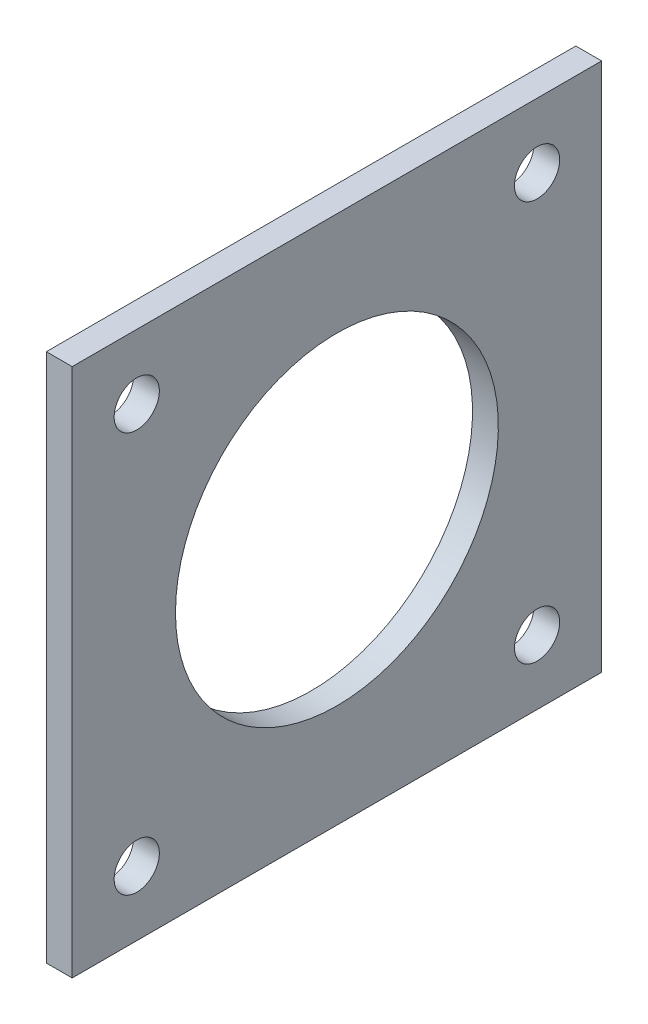
SolidWorks part; units mm, degrees
ref_plane "Front Plane" through (0, 0, 0) normal (0, 0, 1) x (1, 0, 0)
ref_plane "Top Plane" through (0, 0, 0) normal (0, 1, 0) x (1, 0, 0)
ref_plane "Right Plane" through (0, 0, 0) normal (1, 0, 0) x (0, 0, -1)
sketch "Sketch1" plane through (0, 0, 0) normal (0, 1, 0) x (1, 0, 0)
  line L0 (27.5, 55) -> (27.5, 0) construction
  line L1 (5, 0) -> (50, 0)
  line L2 (0, 5) -> (0, 50)
  line L3 (5, 55) -> (50, 55)
  line L4 (55, 5) -> (55, 50)
  line L5 (0, 55) -> (7.5, 55) construction
  line L6 (0, 55) -> (0, 47.5) construction
  line L7 (0, 47.5) -> (7.5, 47.5) construction
  line L8 (7.5, 55) -> (7.5, 47.5) construction
  line L9 (0, 27.5) -> (55, 27.5) construction
  circle A0 centre (7.5, 47.5) radius 2.5
  circle A1 centre (47.5, 47.5) radius 2.5
  circle A2 centre (47.5, 7.5) radius 2.5
  circle A3 centre (7.5, 7.5) radius 2.5
  arc A4 (50, 0) -> (55, 5) centre (50, 5) ccw
  arc A5 (50, 55) -> (55, 50) centre (50, 50) cw
  arc A6 (0, 50) -> (5, 55) centre (5, 50) cw
  arc A7 (5, 0) -> (0, 5) centre (5, 5) cw
  point P23 (55, 55)
  point P29 (0, 0)
  dimension "D3" = 2
  dimension "D5" = 5
  dimension "D1" = 55
  dimension "D2" = 55
  dimension "D4" = 2
extrude "Boss-Extrude2" add sketch "Sketch1" along normal blind 8 and the other way blind 1
sketch "Sketch2" plane through (0, 8, 0) normal (0, 1, 0) x (1, 0, 0)
  line L0 (0, 27.5) -> (55, 27.5)
  line L1 (0, 50) -> (0, 5) construction
  line L2 (55, 5) -> (55, 50) construction
  line L4 (0, 27.5) -> (55, 27.5)
  line L5 (0, 27.5) -> (0, 55)
  line L6 (0, 55) -> (55, 55)
  line L7 (55, 27.5) -> (55, 55)
  circle M3 centre (7.5, 47.5) radius 2.5
  line M5 (55, 5) -> (55, 50)
  arc M6 (55, 50) -> (50, 55) centre (50, 50) ccw
  line M7 (50, 55) -> (5, 55)
  arc M8 (5, 55) -> (0, 50) centre (5, 50) ccw
  line M9 (0, 50) -> (0, 5)
  circle M12 centre (47.5, 47.5) radius 2.5
  dimension "D1" = 27.5
extrude "Cut-Extrude1" cut sketch "Sketch2" against normal through all both and the other way through all contours L0 M9 M5 M6 M7 M8 M12 M3
sketch "Sketch3" plane through (0, 0, -27.5) normal (0, 0, -1) x (-1, 0, 0)
  line L0 (0, -1) -> (0, 8) construction
  line L1 (-55, -1) -> (-37.5, -1) construction
  line L2 (-55, -1) -> (-55, 3.5) construction
  line L3 (-55, 3.5) -> (-37.5, 3.5) construction
  line L4 (-37.5, -1) -> (-37.5, 3.5) construction
  line L5 (0, -1) -> (-55, -1) construction
  circle A0 centre (-37.5, 3.5) radius 3.25
  circle A1 centre (-17.5, 3.5) radius 3.25
  point P10 (0, 3.5)
  dimension "D3" = 6.5
  dimension "D4" = 2
  dimension "D5" = 17.5
  dimension "D1" = 4.5
  dimension "D2" = 17.5
  dimension "D6" = 4.5
sketch3d "3DSketch1"
  point P0 (9.6264, 4.1069, -27.5)
sketch "Sketch5" plane through (0, 8, 0) normal (0, 1, 0) x (1, 0, 0)
  line L0 (27.5, 27.5) -> (27.5, 0)
  line L1 (0, 27.5) -> (55, 27.5) construction
  line L2 (5, 0) -> (50, 0) construction
  line L3 (27.5, 27.5) -> (27.5, 24)
  line L5 (27.5, 24) -> (23, 24)
  line L6 (27.5, 24) -> (27.5, 17.5)
  line L7 (27.5, 17.5) -> (23, 17.5)
  line L8 (23, 24) -> (23, 17.5)
  line L9 (27.5, 24) -> (32, 24)
  line L10 (27.5, 24) -> (27.5, 17.5)
  line L11 (27.5, 17.5) -> (32, 17.5)
  line L12 (32, 24) -> (32, 17.5)
  dimension "D1" = 3.5
  dimension "D2" = 6.5
  dimension "D3" = 4.5
  dimension "D4" = 4.5
  dimension "D5" = 6.5
extrude "Cut-Extrude5" cut sketch "Sketch3" against normal blind 15 draft 0.057 contours A0 | A1
extrude "Boss-Extrude3" add sketch "Sketch5" along normal blind 14.5 contours L5 L8 L7 L0 | L12 L9 L0 L11
sketch "Sketch6" plane through (0, 0, -24) normal (0, 0, -1) x (-1, 0, 0)
  line L0 (-27.5, 8) -> (-27.5, 17)
  line L1 (-32, 8) -> (-23, 8) construction
  circle A0 centre (-27.5, 17) radius 4
  dimension "D2" = 8
  dimension "D1" = 9
extrude "Cut-Extrude4" cut sketch "Sketch6" against normal blind 1.5
sketch "Sketch11" plane through (0, 0, -24) normal (0, 0, -1) x (-1, 0, 0)
  line L0 (-27.5, 22.5) -> (-25.5, 22.5)
  line L1 (-32.4368, 26) -> (-22.5632, 26)
  line L2 (-32, 22.5) -> (-23, 22.5) construction
  line L3 (-25.5, 22.5) -> (-27.5, 22.5)
  line L4 (-25.5, 22.5) -> (-29.5, 22.5)
  line L5 (-25.5, 22.5) -> (-25.5, 26)
  line L6 (-25.5, 26) -> (-29.5, 26)
  line L7 (-29.5, 22.5) -> (-29.5, 26)
  line L8 (-22.5632, 26) -> (-25.5, 22.5)
  line L9 (-29.5, 22.5) -> (-32.4368, 26)
  point P10 (-27.5, 26)
  line M9 (-23, 22.5) -> (-32, 22.5)
  dimension "D1" = 2
  dimension "D2" = 4
  dimension "D3" = 3.5
  dimension "D4" = 40
sketch "Sketch12" plane through (0, 8, 0) normal (0, 1, 0) x (1, 0, 0)
  line L0 (27.5, 17.5) -> (27.5, 0)
  line L1 (32, 17.5) -> (23, 17.5) construction
  line L2 (5, 0) -> (50, 0) construction
  line L3 (17, 0) -> (17, -30)
  line L4 (17, 0) -> (38, 0)
  line L5 (27.5, 0) -> (27.5, -30)
  line L6 (17, -30) -> (38, -30)
  line L7 (38, 0) -> (38, -30)
  point P9 (23.9675, 0)
  line M9 (5, 0) -> (50, 0)
  dimension "D1" = 30
  dimension "D2" = 10.5
extrude "Boss-Extrude7" add sketch "Sketch12" against normal blind 9 contours L7 L5 L6 M9 | L3 L6 L5 M9
sketch "Sketch15" plane through (0, 22.5, 0) normal (0, 1, 0) x (1, 0, 0)
  line L0 (32, 24) -> (32, 17.5) construction
  line L1 (32, 17.5) -> (23, 17.5)
  line L2 (32, 17.5) -> (32, 24)
  line L3 (32, 24) -> (23, 24)
  line L4 (23, 17.5) -> (23, 24)
  line L5 (32, 17.5) -> (23, 17.5) construction
extrude "Boss-Extrude8" add sketch "Sketch15" along normal blind 3.5
extrude "Boss-Extrude9" add sketch "Sketch11" against normal blind 54 contours L9 L7 L1 | L7 L5 L1 M9 | L8 L1 L5
fillet "Fillet4" radius 5 1 edges at (27.5, -1, 30)
sketch "Sketch18" plane through (0, 26, 0) normal (0, 1, 0) x (1, 0, 0)
  line L0 (32.4368, -30) -> (32.4368, 24) construction
  line L1 (22.5632, 24) -> (32.4368, 24)
  line L2 (22.5632, 24) -> (22.5632, 17.5)
  line L3 (22.5632, 17.5) -> (32.4368, 17.5)
  line L4 (32.4368, 24) -> (32.4368, 17.5)
  dimension "D1" = 6.5
extrude "Boss-Extrude11" add sketch "Sketch18" along normal blind 0.5
sketch "Sketch20" plane through (0, 8, 0) normal (0, 1, 0) x (1, 0, 0)
  line L0 (27.5, -1030) -> (27.5, 48970) construction
  line L1 (17, -30) -> (38, -30) construction
  line L2 (32, 17.5) -> (23, 17.5) construction
  line L3 (27.5, 17.5) -> (16.5, 17.5)
  line L4 (27.5, 17.5) -> (27.5, 0)
  line L5 (27.5, 0) -> (16.5, 0)
  line L6 (16.5, 17.5) -> (16.5, 0)
  line L7 (27.5, 17.5) -> (16.5, 0) construction
  line L8 (27.5, 0) -> (16.5, 17.5) construction
  line L10 (27.5, 17.5) -> (38.5, 17.5)
  line L11 (27.5, 17.5) -> (27.5, 0)
  line L12 (27.5, 0) -> (38.5, 0)
  line L13 (38.5, 17.5) -> (38.5, 0)
  line L14 (27.5, 17.5) -> (38.5, 0) construction
  line L15 (27.5, 0) -> (38.5, 17.5) construction
  line L16 (38.5, 17.5) -> (42.5, 17.5)
  line L17 (38.5, 17.5) -> (38.5, 0)
  line L18 (38.5, 0) -> (42.5, 0)
  line L19 (42.5, 17.5) -> (42.5, 0)
  line L21 (16.5, 17.5) -> (12.5, 17.5)
  line L22 (16.5, 17.5) -> (16.5, 0)
  line L23 (16.5, 0) -> (12.5, 0)
  line L24 (12.5, 17.5) -> (12.5, 0)
  line L26 (42.5, 0) -> (38.5, 0)
  line L27 (42.5, 0) -> (42.5, 17.5)
  line L28 (42.5, 17.5) -> (38.5, 17.5)
  line L29 (38.5, 0) -> (38.5, 17.5)
  line L30 (16.5, 0) -> (12.5, 0)
  line L31 (16.5, 0) -> (16.5, 17.5)
  line L32 (16.5, 17.5) -> (12.5, 17.5)
  line L33 (12.5, 0) -> (12.5, 17.5)
  point P5 (27.5, -30)
  point P9 (22, 8.75)
  point P14 (33, 8.75)
  line M12 (5, 0) -> (17, 0)
  line M16 (38, 0) -> (50, 0)
  dimension "D2" = 11
  dimension "D3" = 17.5
  dimension "D4" = 4
extrude "Boss-Extrude12" add sketch "Sketch20" along normal blind 18 contours L21 L24 L6 M12 | L19 L16 L13 M16
sketch "Sketch21" plane through (12.5, 0, 0) normal (-1, 0, 0) x (0, 0, 1)
  line L0 (-17.5, 26) -> (-17.5, 8) construction
  line L1 (0, 26) -> (-17.5, 26)
  line L2 (0, 26) -> (0, 24)
  line L3 (0, 24) -> (-17.5, 24)
  line L4 (-17.5, 26) -> (-17.5, 24)
  dimension "D1" = 2
sketch "Sketch22" plane through (12.5, 0, 0) normal (-1, 0, 0) x (0, 0, 1)
  line L1 (-17.5, 24) -> (0, 24)
  line L2 (-17.5, 24) -> (-17.5, 28)
  line L3 (-17.5, 28) -> (0, 28)
  line L4 (0, 24) -> (0, 28)
  dimension "D1" = 4
extrude "Boss-Extrude13" add sketch "Sketch22" along normal blind 11 and the other way blind 4 contours L3 L4 L1 L2
sketch "Sketch25" plane through (0, 28, 0) normal (0, 1, 0) x (1, 0, 0)
  line L2 (1.5, 17.5) -> (16.5, 17.5) construction
  line L3 (1.5, 0) -> (3.5, 0)
  line L4 (1.5, 0) -> (1.5, 17.5)
  line L5 (1.5, 17.5) -> (3.5, 17.5)
  line L6 (3.5, 0) -> (3.5, 17.5)
  dimension "D1" = 2
extrude "Boss-Extrude14" add sketch "Sketch25" along normal blind 41
sketch "Sketch28" plane through (1.5, 0, 0) normal (-1, 0, 0) x (0, 0, 1)
  line L2 (0, 69) -> (-41, 69)
  line L3 (0, 69) -> (0, 24)
  line L4 (0, 24) -> (-41, 24)
  line L5 (-41, 69) -> (-41, 24)
  dimension "D1" = 45
  dimension "D2" = 41
extrude "Boss-Extrude15" add sketch "Sketch28" against normal blind 2
sketch "Sketch29" plane through (1.5, 0, 0) normal (-1, 0, 0) x (0, 0, 1)
  line L1 (0, 24) -> (-5, 24)
  line L2 (0, 24) -> (0, 33)
  line L3 (0, 33) -> (-5, 33)
  line L4 (-5, 24) -> (-5, 33)
  circle A0 centre (-5, 33) radius 1.75
  circle A1 centre (-36, 33) radius 1.75
  circle A2 centre (-36, 64) radius 1.75
  circle A3 centre (-5, 64) radius 1.75
  dimension "D3" = 3.5
  dimension "D6" = 31
  dimension "D1" = 9
  dimension "D2" = 5
  dimension "D7" = 31
  dimension "D4" = 2
  dimension "D5" = 2
extrude "Cut-Extrude8" cut sketch "Sketch29" against normal blind 9 contours A1 | A3 | A0 | A2
sketch "Sketch30" plane through (42.5, 0, 0) normal (1, 0, 0) x (0, 0, -1)
  line L0 (17.5, 26) -> (17.5, 8) construction
  line L1 (0, 26) -> (17.5, 26)
  line L2 (0, 26) -> (0, 24)
  line L3 (0, 24) -> (17.5, 24)
  line L4 (17.5, 26) -> (17.5, 24)
  line L6 (0, 24) -> (17.5, 24)
  line L7 (0, 24) -> (0, 28)
  line L8 (0, 28) -> (17.5, 28)
  line L9 (17.5, 24) -> (17.5, 28)
  line M4 (17.5, 8) -> (17.5, 26)
  line M5 (17.5, 26) -> (0, 26)
  line M6 (0, 26) -> (0, 8)
  dimension "D1" = 2
  dimension "D2" = 4
extrude "Boss-Extrude16" add sketch "Sketch30" along normal blind 9 and the other way blind 4 contours L3 M6 M4 M5 | L9 L8 L7 M5
sketch "Sketch31" plane through (3.5, 0, 0) normal (1, 0, 0) x (0, 0, -1)
  line L1 (41, 69) -> (20.5, 69)
  line L2 (41, 69) -> (41, 47)
  line L3 (41, 47) -> (20.5, 47)
  line L4 (20.5, 69) -> (20.5, 47)
  circle A0 centre (20.5, 47) radius 10
  dimension "D3" = 20
  dimension "D1" = 22
  dimension "D2" = 20.5
extrude "Cut-Extrude9" cut sketch "Sketch31" against normal blind 9 contours L4 A0 L3 | L3 A0 L4
sketch "Sketch32" plane through (0, 0, -17.5) normal (0, 0, -1) x (-1, 0, 0)
  line L1 (-16.5, 28) -> (-3.5, 28)
  line L2 (-16.5, 28) -> (-16.5, 24)
  line L3 (-16.5, 24) -> (-3.5, 24)
  line L4 (-3.5, 28) -> (-3.5, 24)
extrude "Boss-Extrude17" add sketch "Sketch32" along normal blind 23.5
sketch "Sketch33" plane through (0, 8, 0) normal (0, 1, 0) x (1, 0, 0)
  line L0 (38.5, 17.5) -> (38.5, 0)
  line L1 (38.5, 17.5) -> (38, 17.5)
  line L2 (38.5, 0) -> (38, 0)
  line L3 (38, 17.5) -> (38, 0)
  line L4 (16.5, 17.5) -> (16.5, 0)
  line L5 (16.5, 17.5) -> (17, 17.5)
  line L6 (16.5, 0) -> (17, 0)
  line L7 (17, 17.5) -> (17, 0)
  dimension "D1" = 0.5
  dimension "D2" = 0.5
extrude "Boss-Extrude18" add sketch "Sketch33" along normal blind 20
sketch "Sketch34" plane through (0, 0, 0) normal (0, 0, 1) x (1, 0, 0)
  line L0 (42.5, 24) -> (42.5, 8) construction
  line L1 (51.5, 28) -> (42.5, 28)
  line L2 (51.5, 28) -> (51.5, 24)
  line L3 (51.5, 24) -> (42.5, 24)
  line L4 (42.5, 28) -> (42.5, 24)
  line L5 (42.5, 24) -> (51.5, 24) construction
  line L7 (42.5, 28) -> (38, 28)
  line L8 (42.5, 28) -> (42.5, -1)
  line L9 (42.5, -1) -> (38, -1)
  line L10 (38, 28) -> (38, -1)
  line L11 (17, 28) -> (1.5, 28)
  line L12 (17, 28) -> (17, 24)
  line L13 (17, 24) -> (1.5, 24)
  line L14 (1.5, 28) -> (1.5, 24)
  line L15 (12.5, 24) -> (17, 24)
  line L16 (12.5, 24) -> (12.5, -1)
  line L17 (12.5, -1) -> (17, -1)
  line L18 (17, 24) -> (17, -1)
  line M1 (42.5, 8) -> (42.5, 24)
  line M2 (42.5, 24) -> (51.5, 24)
  line M3 (51.5, 24) -> (51.5, 28)
  line M4 (51.5, 28) -> (38, 28)
  line M5 (38, 28) -> (38, 8)
  line M6 (38, 8) -> (38, -1)
  line M7 (38, -1) -> (50, -1)
extrude "Boss-Extrude19" add sketch "Sketch34" along normal blind 26 contours L18 L13 L16 L17 | L11 L14 L13 L12 | L8 L4 M1 M4 M5 M6 M7 | L4 M4 M2 M3
sketch "Sketch35" plane through (0, 0, -17.5) normal (0, 0, 1) x (1, 0, 0)
  line L1 (32.4368, 26.5) -> (22.5632, 26.5)
  line L2 (32.4368, 26.5) -> (32.4368, 26)
  line L3 (32.4368, 26) -> (22.5632, 26)
  line L4 (22.5632, 26.5) -> (22.5632, 26)
extrude "Boss-Extrude20" add sketch "Sketch35" along normal blind 47.5
sketch "Sketch37" plane through (0, 0, -17.5) normal (0, 0, 1) x (1, 0, 0)
  line L0 (27.5, 8) -> (29.5, 8)
  line L2 (32, 8) -> (23, 8) construction
  line L3 (29.5, 12) -> (33.1362, 7.6666)
  line L4 (29.5, 8) -> (25.5, 8)
  line L5 (29.5, 8) -> (29.5, 12)
  line L6 (29.5, 12) -> (25.5, 12)
  line L7 (25.5, 8) -> (25.5, 12)
  line L8 (25.5, 12) -> (21.8638, 7.6666)
  line L9 (21.8638, 7.6666) -> (33.1362, 7.6666)
  line M8 (32, 8) -> (32, 25.4794)
  line M12 (23, 25.4794) -> (23, 8)
  line M13 (23, 8) -> (32, 8)
  dimension "D1" = 2
  dimension "D2" = 4
  dimension "D3" = 4
  dimension "D4" = 40
  dimension "D5" = 40
extrude "Boss-Extrude21" add sketch "Sketch37" along normal blind 47.5 contours L7 L8 M12 M13 | L7 L5 L6 M13 | L5 L3 M13 M8 | L8 L9 L3 M8 M13 M12
sketch "Sketch38" plane through (0, 0, 30) normal (0, 0, 1) x (1, 0, 0)
  line L1 (22.5632, 26.5) -> (22.1436, 26.5)
  line L2 (22.5632, 26.5) -> (22.5632, 8)
  line L3 (22.5632, 8) -> (22.1436, 8)
  line L4 (22.1436, 26.5) -> (22.1436, 8)
  line L5 (32.4368, 26.5) -> (32.8564, 26.5)
  line L6 (32.4368, 26.5) -> (32.4368, 8)
  line L7 (32.4368, 8) -> (32.8564, 8)
  line L8 (32.8564, 26.5) -> (32.8564, 8)
extrude "Cut-Extrude10" cut sketch "Sketch38" against normal blind 90.5
sketch "Sketch39" plane through (0, 0, 30) normal (0, 0, 1) x (1, 0, 0)
  line L0 (27.784, 26.1035) -> (27.5, 26.5)
  line L1 (32.4368, 26.5) -> (38, 26.5)
  line L2 (32.4368, 26.5) -> (32.4368, 8)
  line L3 (32.4368, 8) -> (38, 8)
  line L4 (38, 26.5) -> (38, 8)
  line L5 (32.4368, 26.5) -> (22.5632, 26.5) construction
  line L6 (27.5, 26.5) -> (27.5, 8)
  line L7 (38, 17.25) -> (38, 19.25)
  line L8 (34, 19.25) -> (38, 22.6064)
  line L9 (38, 19.25) -> (34, 19.25)
  line L10 (38, 19.25) -> (38, 15.25)
  line L11 (38, 15.25) -> (34, 15.25)
  line L12 (34, 19.25) -> (34, 15.25)
  line L13 (34, 15.25) -> (38, 11.8936)
  line L14 (22.5632, 8.5) -> (21.9673, 8)
  line L15 (17, 8) -> (22.5632, 8) construction
  line L16 (17, 22.6064) -> (17.7151, 22.6064)
  line L17 (38, 22.6064) -> (37.2849, 22.6064)
  line L18 (38, 22.6064) -> (38, 22.0064)
  line L19 (38, 22.0064) -> (37.2849, 22.0064)
  line L20 (37.2849, 22.6064) -> (37.2849, 22.0064)
  line L21 (38, 11.8936) -> (37.2849, 11.8936)
  line L22 (38, 11.8936) -> (38, 12.4936)
  line L23 (38, 12.4936) -> (37.2849, 12.4936)
  line L24 (37.2849, 11.8936) -> (37.2849, 12.4936)
  line L25 (17.7151, 22.6064) -> (17.7151, 22.0064)
  line L26 (17, 22.0064) -> (17.7151, 22.0064)
  line L27 (21, 19.25) -> (17, 22.6064)
  line L28 (21, 19.25) -> (21, 15.25)
  line L29 (17, 19.25) -> (21, 19.25)
  line L30 (17.7151, 11.8936) -> (17.7151, 12.4936)
  line L31 (17, 11.8936) -> (17.7151, 11.8936)
  line L32 (17, 12.4936) -> (17.7151, 12.4936)
  line L33 (17, 26.5) -> (17, 8)
  line L34 (17, 15.25) -> (21, 15.25)
  line L35 (21, 15.25) -> (17, 11.8936)
  line L36 (17, 19.25) -> (17, 22.0064)
  line L37 (17, 22.0064) -> (17.7151, 22.0064)
  line L38 (17.7151, 22.0064) -> (21, 19.25)
  line L39 (17, 19.25) -> (21, 19.25)
  dimension "D1" = 2
  dimension "D2" = 4
  dimension "D3" = 4
  dimension "D4" = 40
  dimension "D5" = 40
  dimension "D6" = 0.6
  dimension "D7" = 0.6
extrude "Boss-Extrude23" add sketch "Sketch39" against normal blind 47.5 contours L26 L33 L29 L27 | L33 L34 L28 L29 | L35 L34 L33 L32 | L23 L4 L11 L13 | L9 L12 L11 L4 | L4 L19 L8 L9
ref_plane "Plane1" through (5, 8, 0) normal (0, 1, 0) x (1, 0, 0)
sketch "Sketch45" plane through (0, 8, 0) normal (0, 1, 0) x (1, 0, 0)
  line L0 (0, 15.4413) -> (0, -89.262) construction
  line L1 (-11, 15.4413) -> (-11, -89.262)
  dimension "D1" = 11
sketch "Sketch46" plane through (0, 0, 0) normal (-1, 0, 0) x (0, 0, 1)
  line L1 (-27.5, -1) -> (-5, -1)
  line L2 (-27.5, -1) -> (-27.5, 8)
  line L3 (-27.5, 8) -> (-5, 8)
  line L4 (-5, -1) -> (-5, 8)
  line L5 (-27.5, 8) -> (0, 8)
  line L6 (-27.5, 8) -> (-27.5, -1)
  line L7 (-27.5, -1) -> (0, -1)
  line L8 (0, 8) -> (0, -1)
  line M2 (-27.5, 8) -> (-27.5, -1)
  line M3 (-27.5, -1) -> (-5, -1)
  line M4 (-5, -1) -> (-5, 8)
  line M5 (-5, 8) -> (-27.5, 8)
  dimension "D1" = 27.5
extrude "Boss-Extrude26" add sketch "Sketch46" against normal blind 11.5 contours M5 M2 M3 M4 | L8 L5 L7 M4
sketch "Sketch47" plane through (0, 0, 0) normal (-1, 0, 0) x (0, 0, 1)
  line L1 (-27.5, 8) -> (0, 8)
  line L2 (-27.5, 8) -> (-27.5, -1)
  line L3 (-27.5, -1) -> (0, -1)
  line L4 (0, 8) -> (0, -1)
extrude "Boss-Extrude27" add sketch "Sketch47" along normal blind 11
sketch "Sketch48" plane through (0, 8, 0) normal (0, 1, 0) x (1, 0, 0)
  line L0 (12.5, 17.5) -> (12.5, 24)
  line L1 (23, 24) -> (12.5, 24)
  line L2 (23, 24) -> (23, 17.5)
  line L3 (23, 17.5) -> (12.5, 17.5)
  line L4 (12.5, 24) -> (12.5, 17.5)
  line L5 (12.5, 17.5) -> (7.5, 17.5)
  line L6 (12.5, 24) -> (7.5, 24)
  line L7 (7.5, 17.5) -> (7.5, 24)
  line L8 (42.5, 24) -> (42.5, 17.5)
  line L9 (32, 24) -> (42.5, 24)
  line L10 (32, 24) -> (32, 17.5)
  line L11 (32, 17.5) -> (42.5, 17.5)
  line L12 (42.5, 24) -> (42.5, 17.5)
  line L13 (42.5, 24) -> (47.5, 24)
  line L14 (42.5, 17.5) -> (47.5, 17.5)
  line L15 (47.5, 24) -> (47.5, 17.5)
  line M3 (12.5, 17.5) -> (17, 17.5)
  line M8 (22.5632, 17.5) -> (23, 17.5)
  line M9 (23, 17.5) -> (23, 24)
  line M11 (32, 24) -> (32, 17.5)
  line M12 (32, 17.5) -> (32.4368, 17.5)
  line M17 (38, 17.5) -> (42.5, 17.5)
  dimension "D1" = 5
  dimension "D2" = 5
sketch "Sketch49" plane through (0, 0, -24) normal (0, 0, -1) x (-1, 0, 0)
  line L0 (-17.5, 3.5) -> (-27.5, 17)
  line L1 (-27.5, 17) -> (-17.5, 17)
  line L2 (-17.5, 17) -> (-17.5, 3.5)
  line L3 (-27.5, 17) -> (-37.5, 3.5)
  line L4 (-37.5, 3.5) -> (-37.5, 17)
  line L5 (-37.5, 17) -> (-27.5, 17)
  circle A0 centre (-37.5, 17) radius 4
  circle A1 centre (-17.5, 17) radius 4
  dimension "D1" = 8
  dimension "D2" = 8
extrude "Boss-Extrude31" add sketch "Sketch48" along normal blind 18.5 contours L11 L8 L9 M12 M17 M11 | L15 L13 L8 L14 | L3 L1 L0 M8 M9 M3 | L7 L5 L0 L6
sketch "Sketch50" plane through (0, 0, -24) normal (0, 0, -1) x (-1, 0, 0)
  circle A0 centre (-17.5, 17) radius 4
  circle A1 centre (-37.5, 17) radius 4
  dimension "D1" = 8
  dimension "D2" = 8
extrude "Cut-Extrude11" cut sketch "Sketch50" against normal blind 1.5
sketch "Sketch51" plane through (0, 0, -24) normal (0, 0, -1) x (-1, 0, 0)
  line L1 (-32.4593, 12.5515) -> (-22.8331, 12.5515)
  line L2 (-32.4593, 12.5515) -> (-32.4593, 21.6767)
  line L3 (-32.4593, 21.6767) -> (-22.8331, 21.6767)
  line L4 (-22.8331, 12.5515) -> (-22.8331, 21.6767)
extrude "Boss-Extrude32" add sketch "Sketch51" against normal blind 1.5
sketch "Sketch53" plane through (0, 0, -24) normal (0, 0, -1) x (-1, 0, 0)
  line L0 (-27.5, 17) -> (-27.5, 8)
  line L1 (-47.5, 8) -> (-7.5, 8) construction
  line L2 (-27.5, 8) -> (-27.5, 26.5)
  line L3 (-47.5, 26.5) -> (-16.5, 26.5) construction
  line L4 (-27.5, 17.25) -> (-23.5, 17.25)
  line L5 (-23.5, 17.25) -> (-31.5, 17.25)
  line L7 (-31.5, 13.25) -> (-23.5, 13.25)
  line L8 (-31.5, 13.25) -> (-31.5, 21.25)
  line L9 (-31.5, 21.25) -> (-23.5, 21.25)
  line L10 (-23.5, 13.25) -> (-23.5, 21.25)
  line L11 (-31.5, 13.25) -> (-23.5, 21.25) construction
  line L12 (-31.5, 21.25) -> (-23.5, 13.25) construction
  dimension "D1" = 4
  dimension "D2" = 4
  dimension "D3" = 8
  dimension "D4" = 8
sketch "Sketch54" plane through (0, 0, -17.5) normal (0, 0, 1) x (1, 0, 0)
  line L0 (27.5, 22.5) -> (27.5, 14.5)
  line L1 (29.5, 22.5) -> (25.5, 22.5) construction
  line L3 (23.5, 22.5) -> (31.5, 22.5)
  line L4 (23.5, 22.5) -> (23.5, 14.5)
  line L5 (23.5, 14.5) -> (31.5, 14.5)
  line L6 (31.5, 22.5) -> (31.5, 14.5)
  line L7 (23.5, 22.5) -> (31.5, 14.5) construction
  line L8 (23.5, 14.5) -> (31.5, 22.5) construction
  point P4 (27.5, 18.5)
  line M17 (29.5, 22.5) -> (25.5, 22.5)
  dimension "D1" = 8
  dimension "D2" = 8
  dimension "D3" = 8
extrude "Boss-Extrude35" add sketch "Sketch54" along normal blind 47.5 contours L6 L3 L0 L5 M17 | L4 L5 L0 L3 M17
sketch "Sketch55" plane through (0, 0, 30) normal (0, 0, 1) x (1, 0, 0)
  line L1 (32.4368, 26.5) -> (22.5632, 26.5)
  line L2 (32.4368, 26.5) -> (32.4368, 26)
  line L3 (32.4368, 26) -> (22.5632, 26)
  line L4 (22.5632, 26.5) -> (22.5632, 26)
extrude "Cut-Extrude12" cut sketch "Sketch55" against normal blind 47.5
sketch "Sketch56" plane through (0, 0, 26) normal (0, 0, 1) x (1, 0, 0)
  line L1 (38, 28) -> (37.5, 28)
  line L2 (38, 28) -> (38, 8)
  line L3 (38, 8) -> (37.5, 8)
  line L4 (37.5, 28) -> (37.5, 8)
  line L5 (17, 28) -> (17.5, 28)
  line L6 (17, 28) -> (17, 8)
  line L7 (17, 8) -> (17.5, 8)
  line L8 (17.5, 28) -> (17.5, 8)
  dimension "D1" = 0.5
  dimension "D2" = 0.5
extrude "Boss-Extrude36" add sketch "Sketch56" against normal blind 43.5
sketch "Sketch57" plane through (0, 0, 30) normal (0, 0, 1) x (1, 0, 0)
  line L0 (31.5, 20.5) -> (31.5, 16.5)
  line L1 (35, 18.4644) -> (35, 13.5632)
  line L2 (25.5, 22.5) -> (29.5, 22.5)
  line L3 (29.5, 22.5) -> (32.4368, 26)
  line L4 (29.5, 22.5) -> (29.5, 26)
  line L5 (22.5632, 26) -> (32.4368, 26) construction
  line L6 (31.5, 22.5) -> (31.5, 14.5) construction
  line L7 (35, 13.5632) -> (31.5, 16.5)
  line L8 (31.5, 16.5) -> (35, 16.5)
  line L9 (31.5, 16.5) -> (31.5, 20.4288)
  line L10 (31.5, 20.4288) -> (35, 20.4288)
  line L11 (35, 16.5) -> (35, 20.4288)
  line L12 (35, 18.5356) -> (35, 23.4368)
  line L13 (35, 16.5) -> (31.5, 16.5)
  line L14 (35, 16.5) -> (35, 18.5)
  line L15 (35, 18.5) -> (31.5, 18.5)
  line L16 (31.5, 16.5) -> (31.5, 18.5)
  line L17 (35, 23.4368) -> (31.5, 20.5)
  line L18 (27.5, 22.5) -> (27.5, 14.5) construction
  line L19 (23.5, 14.5) -> (31.5, 14.5) construction
  line L20 (20, 13.5632) -> (23.5, 16.5)
  line L21 (23.5, 16.5) -> (20, 16.5)
  line L22 (20, 18.4644) -> (20, 13.5632)
  line L23 (20, 18.5356) -> (20, 23.4368)
  line L24 (20, 23.4368) -> (23.5, 20.5)
  line L25 (23.5, 20.5) -> (23.5, 16.5)
  line L26 (27.5, 18.5) -> (31.5, 18.5) construction
  line L27 (31.5, 18.5) -> (23.5, 18.5) construction
  line L28 (23.5, 20.5) -> (23.5, 16.5)
  line L29 (32.4368, 26) -> (22.5632, 26)
  line L30 (22.5632, 26) -> (25.5, 22.5)
  line L31 (25.5, 14.5) -> (29.5, 14.5)
  line L32 (22.5632, 11) -> (25.5, 14.5)
  line L33 (32.4368, 11) -> (22.5632, 11)
  line L34 (29.5, 14.5) -> (32.4368, 11)
  line L35 (23.5, 16.5) -> (20, 13.5632)
  line L36 (20, 13.5632) -> (20, 23.4368)
  line L37 (20, 23.4368) -> (23.5, 20.5)
  line L38 (23.5, 18.5) -> (23.5, 20.5)
  line M12 (23.5, 22.5) -> (23.5, 14.5)
  line M13 (23.5, 14.5) -> (31.5, 14.5)
  line M14 (31.5, 14.5) -> (31.5, 22.5)
  dimension "D1" = 2
  dimension "D2" = 3.5
  dimension "D3" = 130
extrude "Boss-Extrude37" add sketch "Sketch57" against normal blind 47.5 contours L12 L17 L0 L10 | L15 L11 L10 L9 | L11 L15 L8 L1 M14 | L8 L7 L1 | L34 L32 L33 M13 | L36 L22 L21 L28 L24 L23 M12 | L21 L22 L20
sketch "Sketch58" plane through (0, 0, 30) normal (0, 0, 1) x (1, 0, 0)
  line L1 (38, 22.0064) -> (37.2849, 22.0064)
  line L2 (38, 22.0064) -> (38, 12.4936)
  line L3 (38, 12.4936) -> (37.2849, 12.4936)
  line L4 (37.2849, 22.0064) -> (37.2849, 12.4936)
  line L5 (17, 22.0064) -> (17.7151, 22.0064)
  line L6 (17, 22.0064) -> (17, 12.4936)
  line L7 (17, 12.4936) -> (17.7151, 12.4936)
  line L8 (17.7151, 22.0064) -> (17.7151, 12.4936)
extrude "Cut-Extrude13" cut sketch "Sketch58" against normal blind 4
sketch "Sketch59" plane through (0, 0, 30) normal (0, 0, 1) x (1, 0, 0)
  line L0 (37.2849, 22.0064) -> (35, 20.0891)
  line L1 (35, 20.0891) -> (35, 14.4109)
  line L2 (35, 14.4109) -> (37.2849, 12.4936)
  line L3 (37.2849, 12.4936) -> (37.2849, 22.0064)
  line L4 (17.7151, 22.0064) -> (20, 20.0891)
  line L5 (20, 20.0891) -> (20, 14.4109)
  line L6 (20, 14.4109) -> (17.7151, 12.4936)
  line L7 (20, 14.4109) -> (17.7151, 12.4936) construction
  line L8 (17.7151, 12.4936) -> (17.7151, 22.0064)
extrude "Cut-Extrude15" cut sketch "Sketch59" against normal blind 47.5
sketch "Sketch60" plane through (0, 0, 26) normal (0, 0, 1) x (1, 0, 0)
  line L0 (17.7151, 12.4936) -> (17.7151, 22.0064) construction
  line L1 (37.2849, 22.0064) -> (37.5, 22.0064)
  line L2 (37.2849, 22.0064) -> (37.2849, 12.4936)
  line L3 (37.2849, 12.4936) -> (37.5, 12.4936)
  line L4 (37.5, 22.0064) -> (37.5, 12.4936)
  line L5 (17.5, 22.0064) -> (17.7151, 22.0064)
  line L6 (17.5, 22.0064) -> (17.5, 12.4936)
  line L7 (17.5, 12.4936) -> (17.7151, 12.4936)
  line L8 (17.7151, 22.0064) -> (17.7151, 12.4936)
extrude "Cut-Extrude16" cut sketch "Sketch60" against normal blind 47.5
sketch "Sketch61" plane through (0, 0, 30) normal (0, 0, 1) x (1, 0, 0)
  line L0 (32.4368, 8) -> (22.5632, 8)
  line L1 (22.5632, 8) -> (22.5632, 8.5)
  line L2 (22.5632, 8.5) -> (24.6609, 11)
  line L3 (24.6609, 11) -> (30.3391, 11)
  line L4 (30.3391, 11) -> (32.4368, 8.5)
  line L5 (32.4368, 8.5) -> (32.4368, 8)
extrude "Cut-Extrude17" cut sketch "Sketch61" against normal blind 47.5
sketch "Sketch62" plane through (0, 0, 30) normal (0, 0, 1) x (1, 0, 0)
  line L1 (23.5, 22.5) -> (31.5, 22.5)
  line L2 (23.5, 22.5) -> (23.5, 14.5)
  line L3 (23.5, 14.5) -> (31.5, 14.5)
  line L4 (31.5, 22.5) -> (31.5, 14.5)
extrude "Cut-Extrude18" cut sketch "Sketch62" against normal blind 47.5
sketch "Sketch63" plane through (0, 0, -41) normal (0, 0, -1) x (-1, 0, 0)
  line L1 (-3.5, 28) -> (-16.5, 28)
  line L2 (-3.5, 28) -> (-3.5, 24)
  line L3 (-3.5, 24) -> (-16.5, 24)
  line L4 (-16.5, 28) -> (-16.5, 24)
extrude "Cut-Extrude20" cut sketch "Sketch63" against normal blind 17
sketch "Sketch64" plane through (0, 0, -17.5) normal (0, 0, -1) x (-1, 0, 0)
  line L1 (-17.5, 26.5) -> (-16.5, 26.5)
  line L2 (-17.5, 26.5) -> (-17.5, 28)
  line L3 (-17.5, 28) -> (-16.5, 28)
  line L4 (-16.5, 26.5) -> (-16.5, 28)
extrude "Boss-Extrude38" add sketch "Sketch64" along normal blind 6.5
sketch "Sketch65" plane through (0, 28, 0) normal (0, 1, 0) x (1, 0, 0)
  line L1 (51.5, 17.5) -> (44.5, 17.5)
  line L2 (51.5, 17.5) -> (51.5, 14.5)
  line L3 (51.5, 14.5) -> (44.5, 14.5)
  line L4 (44.5, 17.5) -> (44.5, 14.5)
  dimension "D1" = 3
  dimension "D2" = 7
extrude "Cut-Extrude21" cut sketch "Sketch65" against normal blind 1.5
sketch "Sketch66" plane through (1.5, 0, 0) normal (-1, 0, 0) x (0, 0, 1)
  line L0 (-10.5, 47) -> (-30.5, 47)
  line L2 (-31.5643, 36.4388) -> (-9.4357, 36.4388)
  line L3 (-31.5643, 36.4388) -> (-31.5643, 57.5612)
  line L4 (-31.5643, 57.5612) -> (-9.4357, 57.5612)
  line L5 (-9.4357, 36.4388) -> (-9.4357, 57.5612)
  line L6 (-31.5643, 36.4388) -> (-9.4357, 57.5612) construction
  line L7 (-31.5643, 57.5612) -> (-9.4357, 36.4388) construction
  circle A0 centre (-20.5, 47) radius 10 construction
  point P5 (-20.5, 47)
  circle M1 centre (-20.5, 47) radius 10
extrude "Boss-Extrude39" add sketch "Sketch66" against normal blind 2 contours L0 M1 | L0 M1
sketch "Sketch67" plane through (1.5, 0, 0) normal (-1, 0, 0) x (0, 0, 1)
  line L0 (0, 28) -> (-41, 28)
  line L1 (-41, 69) -> (-41, 24) construction
  line L2 (-41, 28) -> (-20.5, 28)
  line L3 (-20.5, 28) -> (-20.5, 69)
  line L4 (-41, 69) -> (0, 69) construction
  line L5 (-20.5, 69) -> (-20.5, 48.5)
  line L6 (-20.5, 48.5) -> (-41, 48.5)
  line L7 (-41, 48.5) -> (0, 48.5)
  line L8 (0, 28) -> (0, 69) construction
  circle A0 centre (-20.5, 48.5) radius 12.5
  dimension "D1" = 25
extrude "Cut-Extrude22" cut sketch "Sketch67" against normal blind 155 contours L7 A0 L3 | L3 A0 L7 | L6 A0 L3 | L3 A0 L6
sketch "Sketch68" plane through (1.5, 0, 0) normal (-1, 0, 0) x (0, 0, 1)
  line L1 (0, 28) -> (-41, 28)
  line L2 (0, 28) -> (0, 24)
  line L3 (0, 24) -> (-41, 24)
  line L4 (-41, 28) -> (-41, 24)
  line L5 (-41, 28) -> (62.9975, 28)
  line L6 (-41, 28) -> (-41, -3.7239)
  line L7 (-41, -3.7239) -> (62.9975, -3.7239)
  line L8 (62.9975, 28) -> (62.9975, -3.7239)
  line M8 (-41, 24) -> (26, 24)
  line M9 (26, 24) -> (26, 28)
extrude "Cut-Extrude23" cut sketch "Sketch68" against normal through all and the other way through all contours L8 L5 L6 L7 M9 M8
sketch "Sketch69" plane through (1.5, 0, 0) normal (-1, 0, 0) x (0, 0, 1)
  line L1 (26, 24) -> (0, 24)
  line L2 (26, 24) -> (26, 28)
  line L3 (26, 28) -> (0, 28)
  line L4 (0, 24) -> (0, 28)
  line L5 (0, 28) -> (-41, 28)
  line L6 (0, 28) -> (0, 24)
  line L7 (0, 24) -> (-41, 24)
  line L8 (-41, 28) -> (-41, 24)
  line M7 (-41, 69) -> (-41, 24)
  line M8 (-41, 24) -> (26, 24)
  line M9 (26, 24) -> (26, 28)
  line M10 (26, 28) -> (0, 28)
extrude "Cut-Extrude24" cut sketch "Sketch69" against normal through all contours L4 L5 M7 M8 | L4 M8 M9 M10
